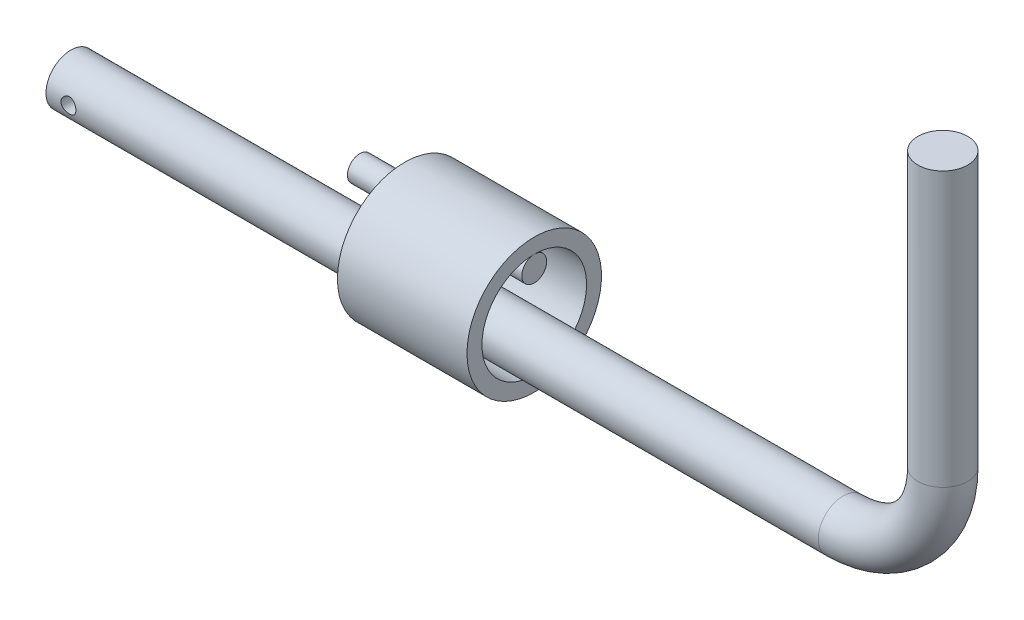
SolidWorks part; units mm, degrees
ref_plane "Спереди" through (0, 0, 0) normal (0, 0, 1) x (1, 0, 0)
ref_plane "Сверху" through (0, 0, 0) normal (0, 1, 0) x (1, 0, 0)
ref_plane "Справа" through (0, 0, 0) normal (1, 0, 0) x (0, 0, -1)
sketch "Эскиз1" plane through (0, 0, 0) normal (0, 0, 1) x (1, 0, 0)
  line L0 (0, 0) -> (155, 0)
  line L1 (175, 20) -> (175, 75)
  arc A0 (155, 0) -> (175, 20) centre (155, 20) ccw
  point P6 (175, 0)
  dimension "D3" = 20
  dimension "D1" = 175
  dimension "D2" = 75
sketch "Эскиз2" plane through (0, 0, 0) normal (1, 0, 0) x (0, 0, -1)
  circle A0 centre (0, 0) radius 5
  dimension "D1" = 10
sweep "По траектории1" add profiles "Эскиз2" path "Эскиз1"
sketch "Эскиз3" plane through (0, 0, 0) normal (0, 0, 1) x (1, 0, 0)
  circle A0 centre (4.5, 0) radius 1.5
  dimension "D1" = 3
  dimension "D2" = 3
extrude "Вырез-Вытянуть1" cut sketch "Эскиз3" against normal through all both and the other way through all
ref_plane "Плоскость1" through (67, 0, 0) normal (-1, 0, 0) x (0, 0, 1)
sketch "Эскиз4" plane through (67, 0, 0) normal (-1, 0, 0) x (0, 0, 1)
  circle A0 centre (0, 5.5) radius 13.5
  circle A1 centre (0, 5.5) radius 10.5
  circle A3 centre (0, 0) radius 5 construction
  dimension "D1" = 21
  dimension "D2" = 27
extrude "Бобышка-Вытянуть1" add sketch "Эскиз4" against normal blind 26 separate body
sketch "Эскиз5" plane through (93, 0, 0) normal (1, 0, 0) x (0, 0, -1)
  circle A0 centre (0, 13.5) radius 2.5
  circle A1 centre (0, 5.5) radius 10.5 construction
  dimension "D1" = 5
extrude "Бобышка-Вытянуть2" add sketch "Эскиз5" against normal blind 35 separate body
